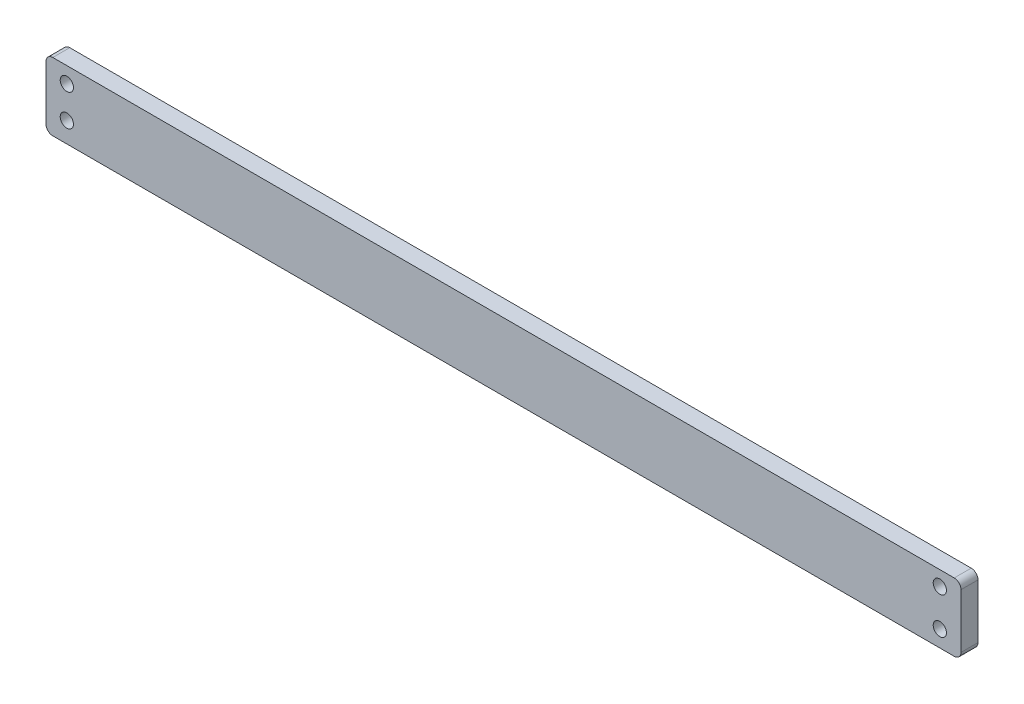
SolidWorks part; units mm, degrees
ref_plane "Front Plane" through (0, 0, 0) normal (0, 0, 1) x (1, 0, 0)
ref_plane "Top Plane" through (0, 0, 0) normal (0, 1, 0) x (1, 0, 0)
ref_plane "Right Plane" through (0, 0, 0) normal (1, 0, 0) x (0, 0, -1)
sketch "Sketch1" plane through (0, 0, 0) normal (0, 0, 1) x (1, 0, 0)
  line L1 (-3.5144, 36.8155) -> (262.0409, 36.8155)
  line L2 (-5.5144, 38.8155) -> (-5.5144, 54.8155)
  line L3 (-3.5144, 56.8155) -> (262.0409, 56.8155)
  line L4 (264.0409, 38.8155) -> (264.0409, 54.8155)
  line L9 (257.7919, 44.0473) -> (257.7919, 49.8213) construction
  circle A0 centre (0.6213, 42.8077) radius 1.95
  circle A1 centre (0.6213, 52.1564) radius 1.95
  circle A2 centre (257.7919, 41.6687) radius 1.95
  circle A3 centre (257.7919, 52.4811) radius 1.95
  arc A4 (-5.5144, 54.8155) -> (-3.5144, 56.8155) centre (-3.5144, 54.8155) cw
  arc A5 (-3.5144, 36.8155) -> (-5.5144, 38.8155) centre (-3.5144, 38.8155) cw
  arc A6 (262.0409, 56.8155) -> (264.0409, 54.8155) centre (262.0409, 54.8155) cw
  arc A7 (262.0409, 36.8155) -> (264.0409, 38.8155) centre (262.0409, 38.8155) ccw
  point P4 (0.6213, 42.8077)
  point P5 (0, 0)
  point P6 (-6.1725, 52.3895)
  point P7 (-6.0081, 52.1342)
  point P8 (-6.0081, 42.8077)
  point P9 (257.7919, 53.9072)
  point P17 (257.7919, 40.9177)
  point P29 (257.7919, 41.6687)
  point P30 (257.7919, 52.4811)
  point P31 (0.6213, 52.1564)
  dimension "D2" = 3.9
  dimension "D3" = 3.9
  dimension "D4" = 3.9
  dimension "D5" = 3.9
  dimension "D6" = 2
  dimension "D1" = 20
extrude "Boss-Extrude1" add sketch "Sketch1" along normal blind 5
